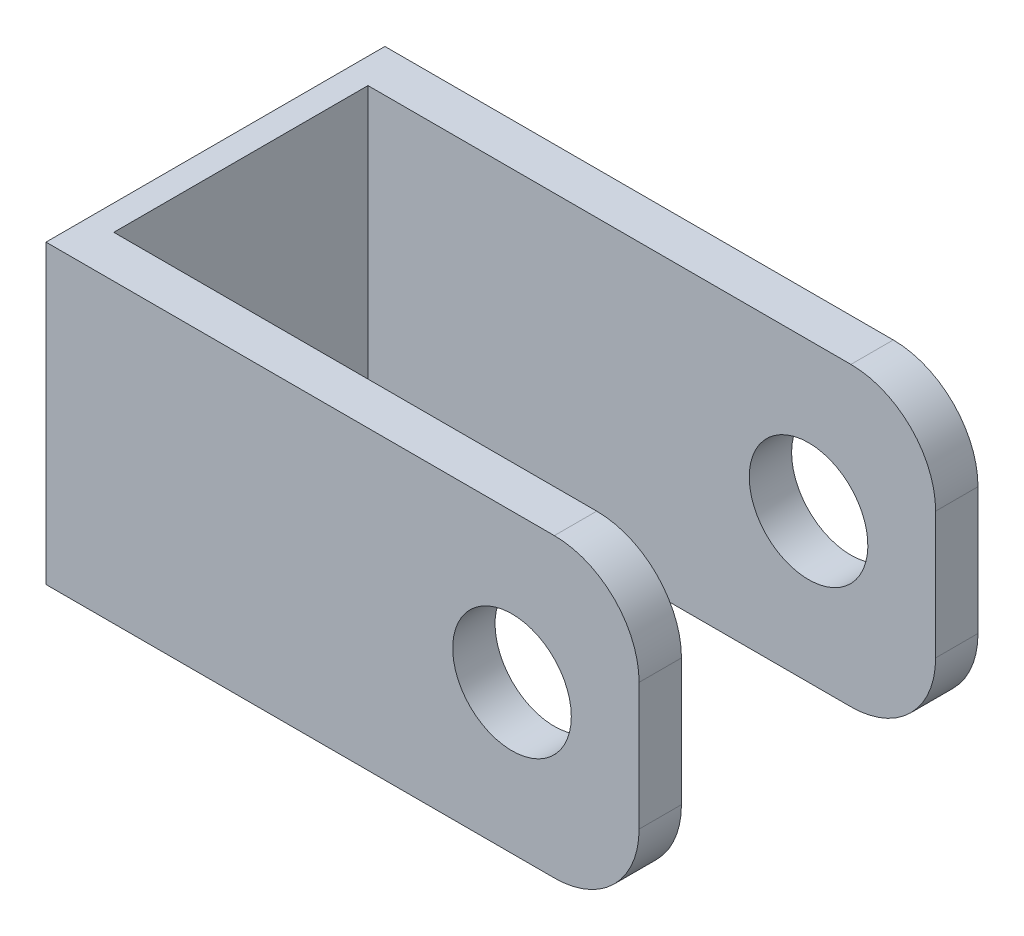
SolidWorks part; units mm, degrees
ref_plane "Front Plane" through (0, 0, 0) normal (0, 0, 1) x (1, 0, 0)
ref_plane "Top Plane" through (0, 0, 0) normal (0, 1, 0) x (1, 0, 0)
ref_plane "Right Plane" through (0, 0, 0) normal (1, 0, 0) x (0, 0, -1)
sketch "Sketch1" plane through (0, 0, 0) normal (1, 0, 0) x (0, 0, -1)
  line L1 (0, 0) -> (-40, 0)
  line L2 (0, 0) -> (0, 35)
  line L3 (0, 35) -> (-40, 35)
  line L4 (-40, 0) -> (-40, 35)
  dimension "D1" = 40
  dimension "D2" = 35
extrude "Boss-Extrude1" add sketch "Sketch1" along normal blind 3
sketch "Sketch2" plane through (0, 0, 0) normal (1, 0, 0) x (0, 0, -1)
  line L0 (-40, 0) -> (0, 0) construction
  line L1 (-40, 35) -> (-35, 35)
  line L2 (-40, 35) -> (-40, 0)
  line L3 (-40, 0) -> (-35, 0)
  line L4 (-35, 35) -> (-35, 0)
  line L6 (0, 35) -> (-5, 35)
  line L7 (0, 35) -> (0, 0)
  line L8 (0, 0) -> (-5, 0)
  line L9 (-5, 35) -> (-5, 0)
  dimension "D1" = 5
  dimension "D2" = 5
extrude "Boss-Extrude2" add sketch "Sketch2" along normal blind 70 contours L2 L1 L4 L3 | L7 L6 L9 L8
fillet "Fillet1" radius 10 4 edges at (70, 0, 2.5) (70, 0, 37.5) (70, 35, 37.5) (70, 35, 2.5)
sketch "Sketch3" plane through (0, 0, 40) normal (0, 0, 1) x (1, 0, 0)
  line L0 (70, 25) -> (70, 10) construction
  circle A0 centre (55, 17.5) radius 7
  point P4 (70, 17.5)
  dimension "D2" = 14
  dimension "D1" = 15
extrude "Cut-Extrude1" cut sketch "Sketch3" against normal blind 120
